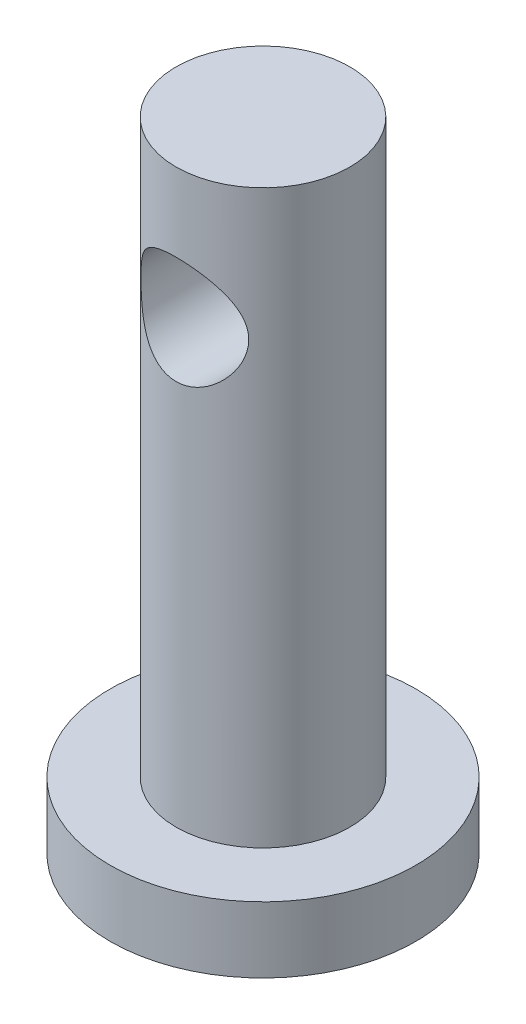
SolidWorks part; units mm, degrees
ref_plane "Front Plane" through (0, 0, 0) normal (0, 0, 1) x (1, 0, 0)
ref_plane "Top Plane" through (0, 0, 0) normal (0, 1, 0) x (1, 0, 0)
ref_plane "Right Plane" through (0, 0, 0) normal (1, 0, 0) x (0, 0, -1)
sketch "Sketch1" plane through (0, 0, 0) normal (0, 1, 0) x (1, 0, 0)
  circle A0 centre (0, 0) radius 3.95
  dimension "D1" = 7.9
extrude "Boss-Extrude1" add sketch "Sketch1" along normal blind 26
sketch "Sketch2" plane through (0, 0, 0) normal (0, 0, 1) x (1, 0, 0)
  line L0 (-3.95, 0) -> (3.95, 0) construction
  circle A0 centre (0, 20) radius 2.45
  dimension "D2" = 4.9
  dimension "D1" = 20
extrude "Cut-Extrude1" cut sketch "Sketch2" against normal through all both and the other way through all
sketch "Sketch3" plane through (0, 0, 0) normal (0, -1, 0) x (1, 0, 0)
  circle A0 centre (0, 0) radius 6.95
  circle A1 centre (0, 0) radius 3.95 construction
  dimension "D1" = 3
extrude "Boss-Extrude2" add sketch "Sketch3" along normal blind 3
